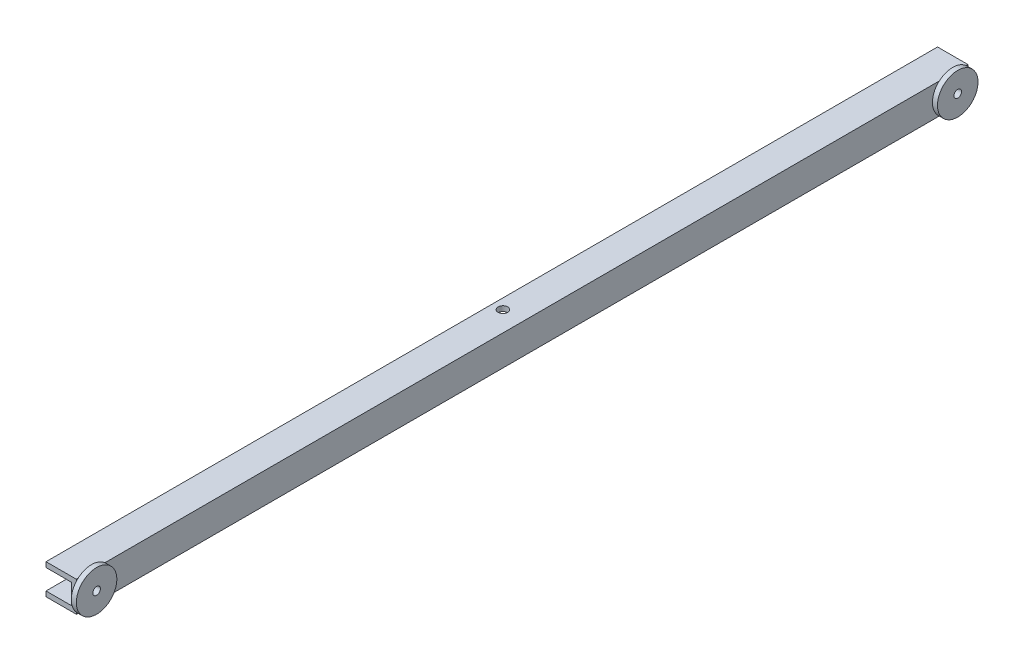
SolidWorks part; units mm, degrees
ref_plane "Front Plane" through (0, 0, 0) normal (0, 0, 1) x (1, 0, 0)
ref_plane "Top Plane" through (0, 0, 0) normal (0, 1, 0) x (1, 0, 0)
ref_plane "Right Plane" through (0, 0, 0) normal (1, 0, 0) x (0, 0, -1)
sketch "Sketch1" plane through (0, 0, 0) normal (0, 0, 1) x (1, 0, 0)
  line L0 (0, -9.525) -> (0, 9.525)
  line L1 (0, 9.525) -> (-19.01, 9.525)
  line L2 (-19.01, 9.525) -> (-19.01, 6.35)
  line L3 (-19.01, 6.35) -> (-3.175, 6.35)
  line L4 (-3.175, 6.35) -> (-3.175, -6.35)
  line L5 (0, 0) -> (-39.0475, 0) construction
  line L6 (-19.01, -6.35) -> (-3.175, -6.35)
  line L7 (-19.01, -9.525) -> (-19.01, -6.35)
  line L8 (0, -9.525) -> (-19.01, -9.525)
  point P4 (0, 0)
  point P12 (-3.175, 0)
  dimension "D1" = 19.05
  dimension "D2" = 19.01
  dimension "D3" = 3.175
  dimension "D4" = 3.175
extrude "Boss-Extrude1" add sketch "Sketch1" against normal blind 558.8
sketch "Sketch2" plane through (0, 9.525, 0) normal (0, 1, 0) x (1, 0, 0)
  line L0 (-19.01, 280.0136) -> (-12.66, 280.0136) construction
  line L1 (-19.01, 558.8) -> (-19.01, 0) construction
  circle A0 centre (-12.66, 280.0136) radius 3
  dimension "D2" = 6
  dimension "D1" = 6.35
extrude "Cut-Extrude1" cut sketch "Sketch2" against normal blind 558.8
sketch "Sketch4" plane through (0, 0, 0) normal (1, 0, 0) x (0, 0, -1)
  line L0 (0, 0) -> (9.525, 0) construction
  line L1 (279.4, 9.525) -> (279.4, -9.525) construction
  line L2 (558.8, 9.525) -> (0, 9.525) construction
  line L3 (558.8, -9.525) -> (0, -9.525) construction
  circle A0 centre (9.525, 0) radius 2.3813
  circle A1 centre (549.275, 0) radius 2.3813
  dimension "D2" = 4.7625
  dimension "D1" = 9.525
extrude "Cut-Extrude8" cut sketch "Sketch4" against normal blind 6.8
sketch "Sketch5" plane through (0, 0, 0) normal (1, 0, 0) x (0, 0, -1)
  circle A0 centre (9.525, 0) radius 12.7
  circle A1 centre (549.275, 0) radius 12.7
  circle A2 centre (9.525, 0) radius 2.3812 construction
  circle A3 centre (9.525, 0) radius 2.3813
  circle A4 centre (549.275, 0) radius 2.3813 construction
  circle A5 centre (549.275, 0) radius 2.3813
  dimension "D1" = 25.4
extrude "Boss-Extrude3" add sketch "Sketch5" along normal blind 3.175
